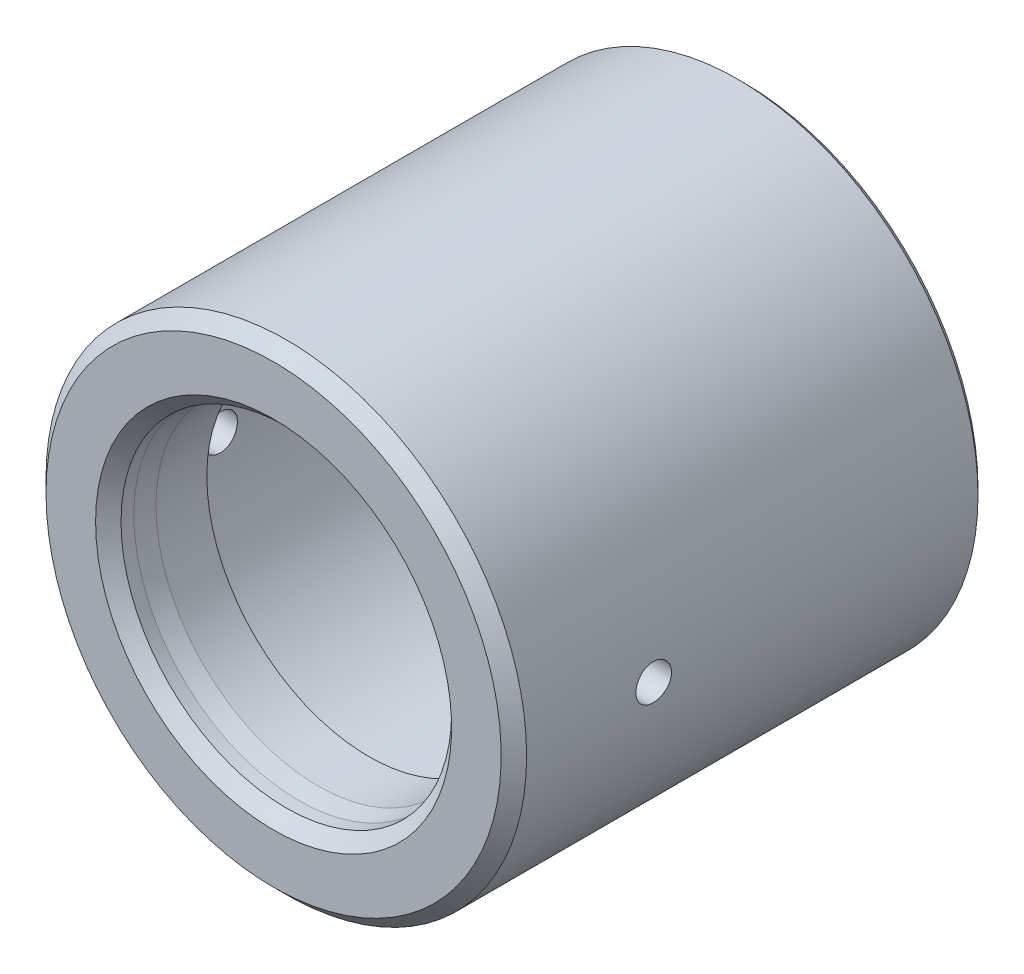
SolidWorks part; units mm, degrees
ref_plane "정면" through (0, 0, 0) normal (0, 0, 1) x (1, 0, 0)
ref_plane "윗면" through (0, 0, 0) normal (0, 1, 0) x (1, 0, 0)
ref_plane "우측면" through (0, 0, 0) normal (1, 0, 0) x (0, 0, -1)
sketch "스케치1" plane through (0, 0, 0) normal (1, 0, 0) x (0, 0, -1)
  line L0 (0, 0) -> (0, 13) construction
  line L1 (0, 13) -> (2, 13)
  line L2 (0, 13) -> (0, 18.9)
  line L3 (0, 18.9) -> (37, 18.9)
  line L4 (37, 18.9) -> (37, 15.25)
  line L5 (37, 15.25) -> (8.9969, 15.25)
  line L6 (0, 0) -> (37, 0) construction
  line L7 (2, 13) -> (3.5, 12.75)
  line L8 (3.5, 12.75) -> (7.5, 12.75)
  line L9 (37, 15.25) -> (37, 0) construction
  line L10 (211.6946, 25) -> (-8.3054, 25) construction
  arc A0 (8.9969, 15.25) -> (7.5, 12.75) centre (11.5478, 12.0245) ccw
  dimension "D1" = 37.8
  dimension "D2" = 30.5
  dimension "D3" = 26
  dimension "D4" = 2.5
  dimension "D5" = 4
  dimension "D6" = 37
  dimension "D7" = 1.5
  dimension "D8" = 220
  dimension "D9" = 2
revolve "회전1" add sketch "스케치1" angle 360 about L6
sketch "스케치2" plane through (0, 0, 0) normal (0, 1, 0) x (1, 0, 0)
  line L0 (0, 25) -> (0, 0) construction
  circle A0 centre (0, 25) radius 2.4
  dimension "D1" = 4.8
  dimension "D2" = 25
extrude "컷-돌출1" cut sketch "스케치2" against normal through all
chamfer "모따기1" distance 0.5 angle 45 1 edges at (18.9, 0, -37)
chamfer "모따기2" distance 1 angle 45 3 edges at (13, 0, 0) (18.9, 0, 0) (15.25, 0, -37)
sketch "스케치3" plane through (0, 0, 0) normal (1, 0, 0) x (0, 0, -1)
  line L0 (0, 0) -> (11, 0) construction
  line L1 (0, 17.9) -> (0, -17.9) construction
  circle A0 centre (11, 0) radius 1.4
  dimension "D1" = 2.8
  dimension "D2" = 3.5
extrude "컷-돌출2" cut sketch "스케치3" against normal through all both and the other way through all
